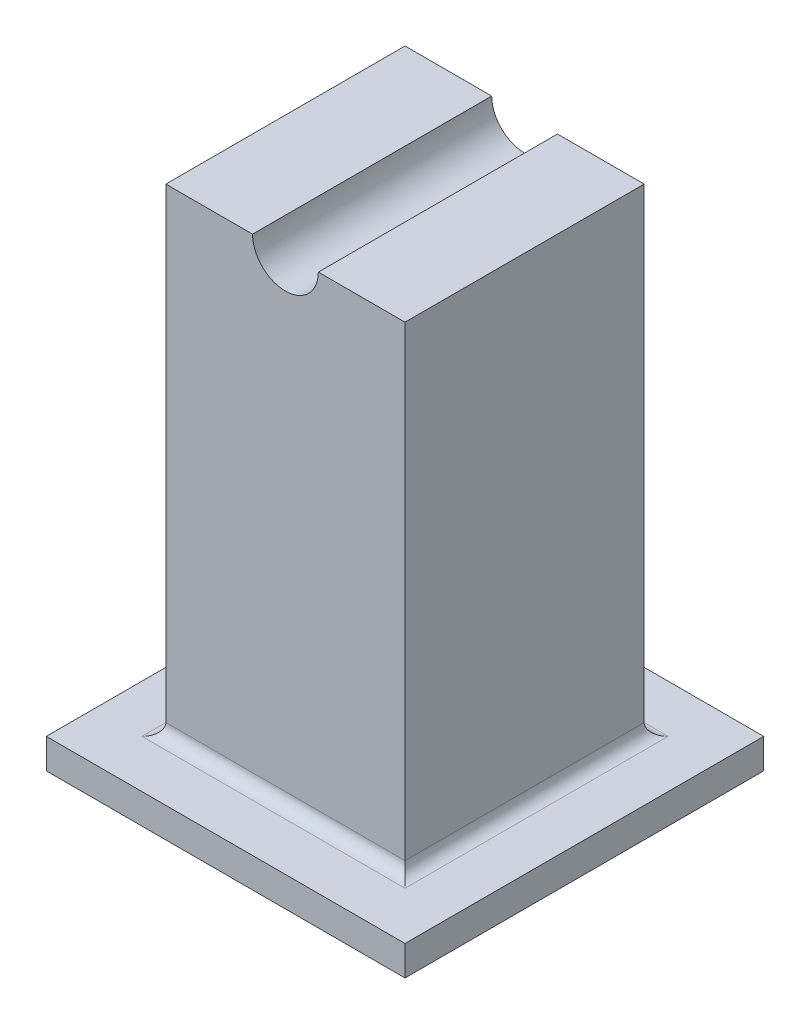
SolidWorks part; units mm, degrees
ref_plane "Front Plane" through (0, 0, 0) normal (0, 0, 1) x (1, 0, 0)
ref_plane "Top Plane" through (0, 0, 0) normal (0, 1, 0) x (1, 0, 0)
ref_plane "Right Plane" through (0, 0, 0) normal (1, 0, 0) x (0, 0, -1)
sketch "Sketch1" plane through (0, 0, 0) normal (0, 0, 1) x (1, 0, 0)
  line L0 (32.385, 107.95) -> (50.8, 107.95)
  line L1 (0, 0) -> (50.8, 0)
  line L2 (0, 0) -> (0, 107.95)
  line L3 (0, 107.95) -> (18.415, 107.95)
  line L4 (50.8, 0) -> (50.8, 107.95)
  line L5 (25.4, 107.95) -> (50.8, 107.95) construction
  line L6 (25.4, 107.95) -> (0, 107.95) construction
  arc A0 (18.415, 107.95) -> (32.385, 107.95) centre (25.4, 107.95) ccw
  dimension "D3" = 13.97
  dimension "D1" = 50.8
  dimension "D2" = 107.95
extrude "Boss-Extrude1" add sketch "Sketch1" along normal blind 50.8
sketch "Sketch2" plane through (0, 0, 0) normal (0, -1, 0) x (1, 0, 0)
  line L0 (0, 50.8) -> (0, 0) construction
  line L1 (6.35, 6.35) -> (44.45, 6.35)
  line L2 (6.35, 6.35) -> (6.35, 44.45)
  line L3 (6.35, 44.45) -> (44.45, 44.45)
  line L4 (44.45, 6.35) -> (44.45, 44.45)
  line L5 (6.35, 6.35) -> (44.45, 44.45) construction
  line L6 (6.35, 44.45) -> (44.45, 6.35) construction
  line L7 (0, 0) -> (50.8, 0) construction
  line L8 (0, 50.8) -> (50.8, 50.8) construction
  line L9 (50.8, 50.8) -> (50.8, 0) construction
  point P0 (25.4, 25.4)
  dimension "D1" = 6.35
  dimension "D2" = 6.35
  dimension "D3" = 6.35
  dimension "D4" = 6.35
extrude "Cut-Extrude1" cut sketch "Sketch2" against normal blind 95.25
sketch "Sketch3" plane through (0, 0, 0) normal (0, -1, 0) x (1, 0, 0)
  line L0 (50.8, 50.8) -> (50.8, 0) construction
  line L1 (63.5, 63.5) -> (-12.7, 63.5)
  line L2 (63.5, 63.5) -> (63.5, -12.7)
  line L3 (63.5, -12.7) -> (-12.7, -12.7)
  line L4 (-12.7, 63.5) -> (-12.7, -12.7)
  line L5 (63.5, 63.5) -> (-12.7, -12.7) construction
  line L6 (63.5, -12.7) -> (-12.7, 63.5) construction
  line L7 (0, 0) -> (50.8, 0) construction
  line L8 (0, 50.8) -> (0, 0) construction
  line L9 (0, 50.8) -> (50.8, 50.8) construction
  line L11 (50.8, 50.8) -> (0, 50.8)
  line L12 (50.8, 50.8) -> (50.8, 0)
  line L13 (50.8, 0) -> (0, 0)
  line L14 (0, 50.8) -> (0, 0)
  point P0 (25.4, 25.4)
  dimension "D1" = 12.7
  dimension "D2" = 12.7
  dimension "D3" = 12.7
  dimension "D4" = 12.7
extrude "Boss-Extrude2" add sketch "Sketch3" against normal blind 6.35
fillet "Fillet1" radius 2.54 4 edges at (25.4, 6.35, 0) (50.8, 6.35, 25.4) (25.4, 6.35, 50.8) (0, 6.35, 25.4)
